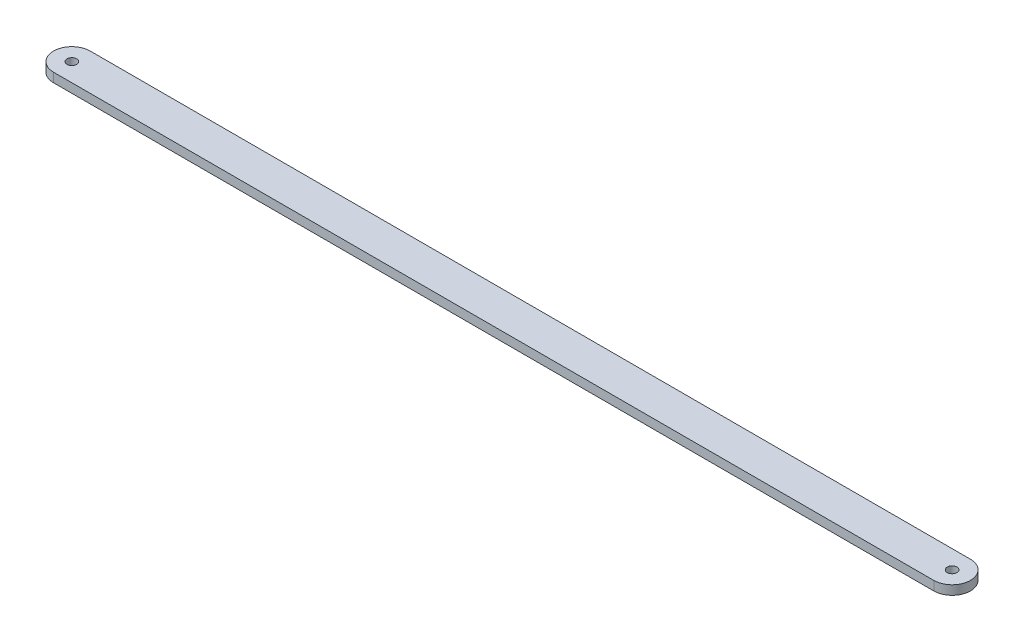
SolidWorks part; units mm, degrees
ref_plane "Front Plane" through (0, 0, 0) normal (0, 0, 1) x (1, 0, 0)
ref_plane "Top Plane" through (0, 0, 0) normal (0, 1, 0) x (1, 0, 0)
ref_plane "Right Plane" through (0, 0, 0) normal (1, 0, 0) x (0, 0, -1)
sketch "Sketch1" plane through (0, 0, 0) normal (0, 1, 0) x (1, 0, 0)
  line L0 (-304.8, 0) -> (304.8, 0) construction
  line L1 (-304.8, 12.7) -> (304.8, 12.7)
  line L2 (-304.8, -12.7) -> (304.8, -12.7)
  arc A0 (-304.8, 12.7) -> (-304.8, -12.7) centre (-304.8, 0) ccw
  arc A1 (304.8, -12.7) -> (304.8, 12.7) centre (304.8, 0) ccw
  circle A2 centre (304.8, 0) radius 3.3655
  circle A3 centre (-304.8, 0) radius 3.3655
  point P2 (0, 0)
  dimension "D3" = 6.731
  dimension "D5" = 6.731
  dimension "D1" = 609.6
  dimension "D2" = 25.4
  dimension "D4" = 0
extrude "Boss-Extrude1" add sketch "Sketch1" along normal blind 6.35
